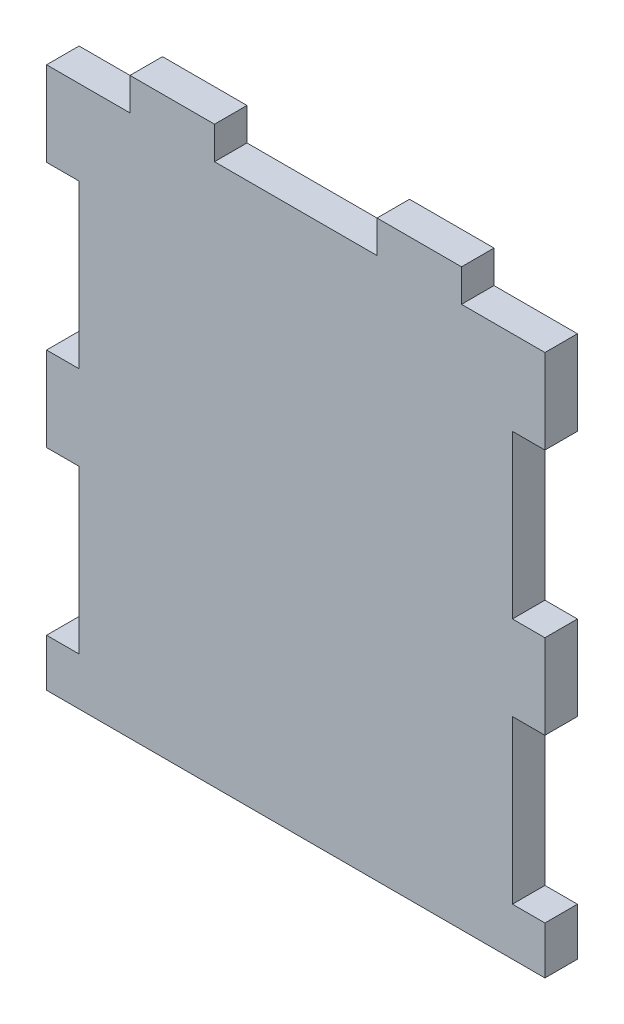
SolidWorks part; units mm, degrees
material "Oak"
ref_plane "Front Plane" through (0, 0, 0) normal (0, 0, 1) x (1, 0, 0)
ref_plane "Top Plane" through (0, 0, 0) normal (0, 1, 0) x (1, 0, 0)
ref_plane "Right Plane" through (0, 0, 0) normal (1, 0, 0) x (0, 0, -1)
sketch "Sketch1" plane through (0, 0, 0) normal (0, 0, 1) x (1, 0, 0)
  line L1 (-40.9935, 16.542) -> (5.0065, 16.542)
  line L2 (-40.9935, 16.542) -> (-40.9935, -33.458)
  line L3 (-40.9935, -33.458) -> (5.0065, -33.458)
  line L4 (5.0065, 16.542) -> (5.0065, -33.458)
  dimension "D1" = 50
  dimension "D2" = 46
extrude "Boss-Extrude1" add sketch "Sketch1" along normal blind 3
sketch "Sketch2" plane through (0, 0, 3) normal (0, 0, 1) x (1, 0, 0)
  line L0 (-40.9935, 16.542) -> (-40.9935, -33.458) construction
  line L1 (-40.9935, 8.742) -> (-37.9935, 8.742)
  line L2 (-40.9935, 8.742) -> (-40.9935, -6.258)
  line L3 (-40.9935, -6.258) -> (-37.9935, -6.258)
  line L4 (-37.9935, 8.742) -> (-37.9935, -6.258)
  line L5 (5.0065, 16.542) -> (-40.9935, 16.542) construction
  line L6 (5.0065, -33.458) -> (5.0065, 16.542) construction
  line L7 (5.0065, 8.742) -> (2.0065, 8.742)
  line L8 (5.0065, 8.742) -> (5.0065, -6.258)
  line L9 (5.0065, -6.258) -> (2.0065, -6.258)
  line L10 (2.0065, 8.742) -> (2.0065, -6.258)
  point P8 (-39.4935, 8.742)
  dimension "D1" = 3
  dimension "D2" = 7.8
  dimension "D3" = 15
  dimension "D4" = 3
  dimension "D5" = 7.8
  dimension "D6" = 15
extrude "Cut-Extrude1" cut sketch "Sketch2" against normal through all
pattern_linear "LPattern1" count 3 spacing 22.8 along (0, -1, 0) of "Cut-Extrude1"
sketch "Sketch3" plane through (0, 16.542, 0) normal (0, 1, 0) x (1, 0, 0)
  line L0 (5.0065, 0) -> (-40.9935, 0) construction
  line L1 (-33.2935, 0) -> (-25.4935, 0)
  line L2 (-33.2935, 0) -> (-33.2935, -3)
  line L3 (-33.2935, -3) -> (-25.4935, -3)
  line L4 (-25.4935, 0) -> (-25.4935, -3)
  line L5 (5.0065, -3) -> (-40.9935, -3) construction
  line L6 (-40.9935, -3) -> (-40.9935, 0) construction
  point P8 (-25.4935, -1.5)
  dimension "D1" = 7.8
  dimension "D2" = 7.7
extrude "Boss-Extrude2" add sketch "Sketch3" along normal blind 3
pattern_linear "LPattern2" count 2 spacing 22.8 along (1, 0, 0) of "Boss-Extrude2"
